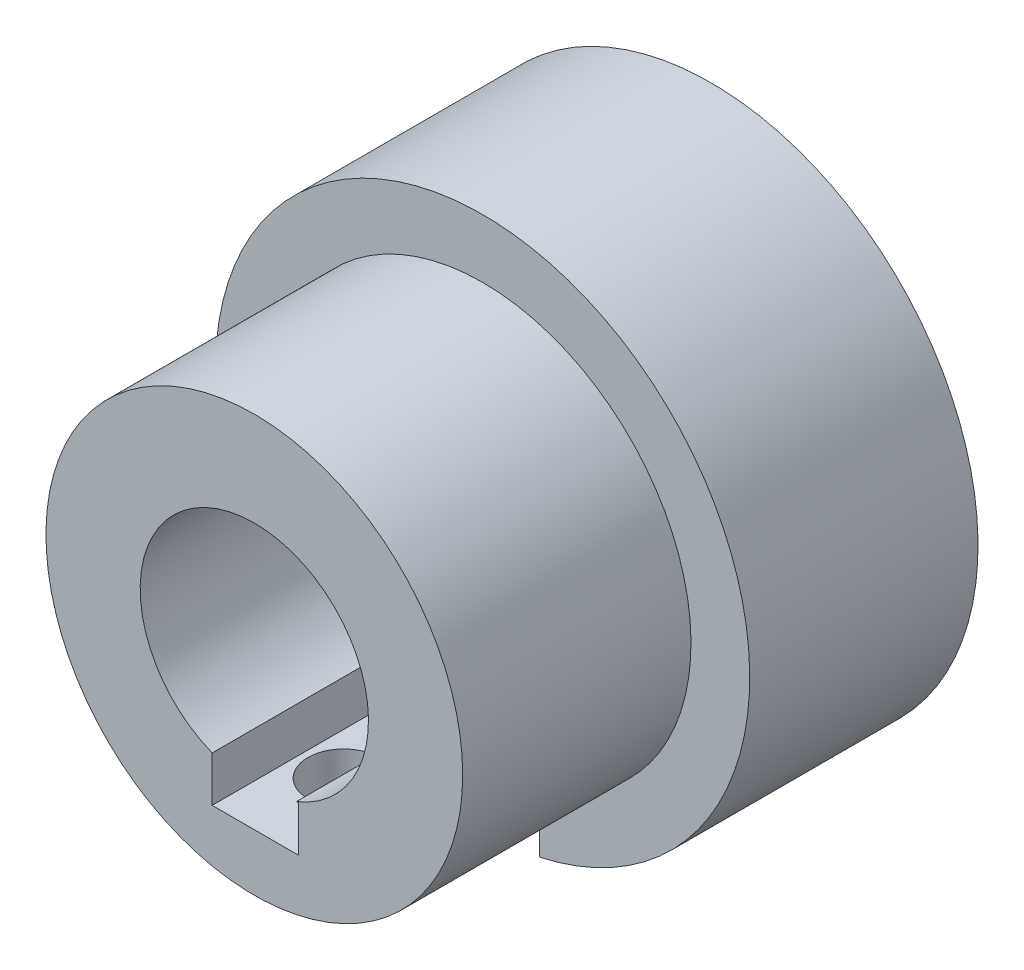
SolidWorks part; units mm, degrees
material "Latón"
ref_plane "Alzado" through (0, 0, 0) normal (0, 0, 1) x (1, 0, 0)
ref_plane "Planta" through (0, 0, 0) normal (0, 1, 0) x (1, 0, 0)
ref_plane "Vista lateral" through (0, 0, 0) normal (1, 0, 0) x (0, 0, -1)
sketch "Croquis1" plane through (0, 0, 0) normal (0, 0, 1) x (1, 0, 0)
  line L1 (-5, -3.5142) -> (5, -3.5142)
  line L2 (-5, -3.5142) -> (-5, -25.3589)
  line L3 (-5, -25.3589) -> (5, -25.3589)
  line L4 (5, -3.5142) -> (5, -25.3589)
  circle A0 centre (0, 0) radius 23.4
  dimension "D1" = 10
  dimension "D3" = 46.8
  dimension "D2" = 5
extrude "Saliente-Extruir1" add sketch "Croquis1" along normal blind 20 contours L4 A0 L2 L1
sketch "Croquis2" plane through (0, 0, 20) normal (0, 0, 1) x (1, 0, 0)
  circle A0 centre (0, 0) radius 18.2535
extrude "Saliente-Extruir2" add sketch "Croquis2" along normal blind 20
sketch "Croquis3" plane through (0, 0, 40) normal (0, 0, 1) x (1, 0, 0)
  line L1 (-3.6927, -9.2932) -> (3.8553, -9.2932)
  line L2 (-3.6927, -9.2932) -> (-3.6927, -13.2718)
  line L3 (-3.6927, -13.2718) -> (3.8553, -13.2718)
  line L4 (3.8553, -9.2932) -> (3.8553, -13.2718)
  circle A0 centre (0, 0) radius 10
  dimension "D1" = 20
extrude "Cortar-Extruir1" cut sketch "Croquis3" against normal blind 20 contours L1 A0
sketch "Croquis4" plane through (0, 0, 0) normal (0, 1, 0) x (1, 0, 0)
  circle A0 centre (0, -32.173) radius 3.1306
extrude "Cortar-Extruir2" cut sketch "Croquis4" against normal blind 20
